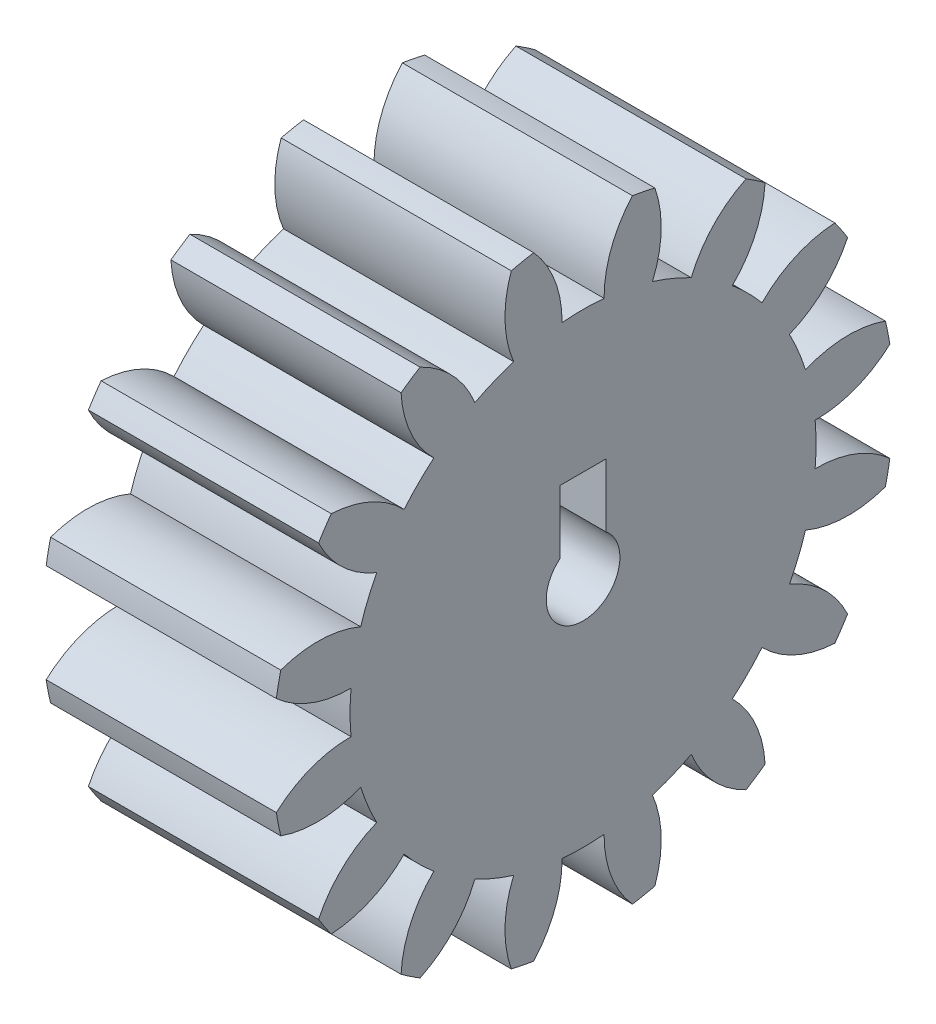
SolidWorks part; units mm, degrees
ref_plane "Plane1" through (0, 0, 0) normal (0, 0, 1) x (1, 0, 0)
ref_plane "Plane2" through (0, 0, 0) normal (0, 1, 0) x (1, 0, 0)
ref_plane "Plane3" through (0, 0, 0) normal (1, 0, 0) x (0, 0, -1)
sketch "HoldingSke" plane through (0, 0, 0) normal (0, 1, 0) x (1, 0, 0)
  line L0 (0, 0) -> (0.6408, -0.1838)
  line L1 (-15, 0) -> (100, 0) construction
  line L2 (0, 0) -> (-2.1039, 2.3779)
  line L3 (0, 0) -> (-11.863, 4.5341)
  line L4 (0, 0) -> (8.3015, 2.3804)
  line L5 (0, 0) -> (-46.8476, -17.4728)
  line L6 (0, 0) -> (-8.2896, -5.593)
  line L7 (-2.1039, 2.3779) -> (8.6586, 51.2059)
  line L8 (-76.2, 54.61) -> (-75.2, 54.61)
  line L9 (-67.7845, 28.3722) -> (-49.3413, 33.142)
  line L10 (-76.2, 71.12) -> (104.1128, 71.12)
  line L11 (0, 0) -> (-10, 0)
  line L12 (-76.2, 101.6) -> (-76.147, 101.6)
  line L13 (24.9733, 27.94) -> (52.9518, 28.4284)
  line L14 (24.9733, 27.94) -> (24.9743, 27.94)
  line L15 (24.9733, 27.94) -> (100.4006, 29.5858)
  line L16 (-63.627, -1.5) -> (-12.827, -1.5)
  circle A0 centre (0, 0) radius 3
  circle A1 centre (0, 0) radius 10.124
  circle A2 centre (0, 0) radius 37.5
  circle A3 centre (0, 0) radius 3
  dimension "MHD" = 20.248
  dimension "Hub_dia" = 75
  dimension "Bore" = 6
  dimension "MBD" = 6
  dimension "Num_teeth" = 16
  dimension "Pitch_radius" = 180.3128
  dimension "Pitch" = 0.6667
  dimension "Width" = 10
  dimension "Overall_len" = 50
  dimension "Show_teeth" = 16
  dimension "Thickness" = 10
  dimension "OAL" = 50.0001
  dimension "T_dim" = 1
  dimension "Ap" = 14.5
  dimension "H" = 19.05
  dimension "Backlash" = 0.053
  dimension "Addendum_fac" = 1
  dimension "Dedendum_fac" = 1.25
  dimension "Clearance_fac" = 0.25
  dimension "Dedendum_add" = 0.001
  dimension "Module" = 1.5
sketch "BasProSke" plane through (0, 0, 0) normal (0, 1, 0) x (1, 0, 0)
  line L0 (-10, 0) -> (60, 0) construction
  line L1 (0, 0) -> (0, 13.5)
  line L2 (0, 0) -> (10, 0)
  line L3 (10, 0) -> (10, 13.5)
  line L4 (10, 13.5) -> (0, 13.5)
  dimension "Diameter" = 27
  dimension "Thickness" = 10
revolve "Base-Revolve" add sketch "BasProSke" angle 360 about L0
sketch "TooCutSke" plane through (0, 0, 0) normal (1, 0, 0) x (0, 0, -1)
  line L1 (0, 0) -> (0, 107) construction
  line L2 (0, 0) -> (-1.2689, 11.9327) construction
  line L3 (0, 0) -> (-4.663, 23.4427) construction
  line L4 (-1.2689, 11.9327) -> (-2.3315, 11.7214) construction
  arc A0 (0.9122, 10.0828) -> (-0.9122, 10.0828) centre (0, 0) ccw
  arc A1 (2.1654, 13.3509) -> (-2.1654, 13.3509) centre (0, 0) ccw
  circle A2 centre (0, 0) radius 12 construction
  circle A3 centre (0, 0) radius 11.6178 construction
  arc A4 (-0.9122, 10.0828) -> (-2.1654, 13.3509) centre (-5.712, 10.1166) ccw
  arc A5 (2.1654, 13.3509) -> (0.9122, 10.0828) centre (5.712, 10.1166) ccw
  dimension "Root_dia" = 20.248
  dimension "Overcut_dia" = 27.0508
  dimension "Pitch_dia" = 24
  dimension "Base_dia" = 23.2355
  dimension "Flank_rad" = 4.8
  dimension "Half_ang" = 11.25
  dimension "Half_CT" = 1.0835
extrude "ToothCut" cut sketch "TooCutSke" along normal through all
fillet "Breaks" [suppressed] radius 0.03
fillet "RootFillets" [suppressed] radius 0.376
pattern_circular "TeethCuts" count 16 every 22.5 about axis through (-10, 0, 0) along (1, 0, 0) of "ToothCut", "RootFillets", "Breaks"
sketch "HubNeaOneSke" [suppressed] plane through (0, 0, 0) normal (-1, 0, 0) x (0, 0, 1)
  circle A0 centre (0, 0) radius 12.7
  dimension "Diameter" = 20.248
extrude "HubNearOne" [suppressed] add sketch "HubNeaOneSke" along normal blind 40.0001
sketch "HubNeaBotSke" [suppressed] plane through (0, 0, 0) normal (-1, 0, 0) x (0, 0, 1)
  circle A0 centre (0, 0) radius 12.7
  dimension "Diameter" = 20.248
extrude "HubNearBoth" [suppressed] add sketch "HubNeaBotSke" along normal blind 20
ref_plane "FarPln" through (10, 0, 0) normal (1, 0, 0) x (0, 0, -1)
sketch "HubFarSke" [suppressed] plane through (12.7, 0, 0) normal (1, 0, 0) x (0, 0, -1)
  circle A0 centre (0, 0) radius 12.7
  dimension "Diameter" = 20.248
extrude "HubFar" [suppressed] add sketch "HubFarSke" along normal blind 20
sketch "BorSke" plane through (0, 0, 0) normal (1, 0, 0) x (0, 0, -1)
  circle A0 centre (0, 0) radius 3
  dimension "Diameter" = 6
extrude "Bore" cut sketch "BorSke" along normal mid plane 100.0001
sketch "KeySke" plane through (0, 0, 0) normal (1, 0, 0) x (0, 0, -1)
  line L0 (-1, 0) -> (-1, 4)
  line L1 (-1, 4) -> (1, 4)
  line L2 (1, 4) -> (1, 0)
  line L3 (0, 0) -> (0, 34) construction
  line L4 (-1, 0) -> (1, 0)
  dimension "Offset" = 4
  dimension "Width" = 2
extrude "Keyway" cut sketch "KeySke" along normal mid plane 100.0001
pattern_circular "Keyway2" [suppressed] count 2 every 90 about axis through (-10, 0, 0) along (1, 0, 0)
sketch "Sketch1" plane through (10, 0, 0) normal (1, 0, 0) x (0, 0, -1)
  line L0 (-1, 4) -> (-1, 2.8284) construction
  line L1 (1, 4) -> (-1, 4) construction
  line L2 (1, 2.8284) -> (1, 4) construction
  line L3 (-1, 4) -> (-1, 1.249)
  line L4 (1, 4) -> (-1, 4)
  line L5 (1, 1.249) -> (1, 4)
  arc A0 (-1, 1.249) -> (1, 1.249) centre (0, 0) ccw
  circle A1 centre (0, 0) radius 5.6987
  dimension "D1" = 3.2
extrude "Boss-Extrude1" add sketch "Sketch1" against normal through all
equation "' \"Module@HoldingSke\" = 6.35"
equation "' \"Num_teeth@HoldingSke\" = 12"
equation "' \"Ap@HoldingSke\" =  20"
equation "' \"Width@HoldingSke\" = 0.5 * 25.4"
equation "' \"Hub_dia@HoldingSke\"= 1 * 25.4"
equation "' \"Overall_len@HoldingSke\" = 1.0 * 25.4"
equation "' \"Bore@HoldingSke\" = 0.75 * 25.4"
equation "' \"T_dim@HoldingSke\" = 0.1 * 25.4"
equation "' \"Width@KeySke\" = 0.25 * 25.4"
equation "' \"Show_teeth@HoldingSke\" = 13"
equation "' \"Backlash@HoldingSke\" = 0.009 * 25.4"
equation "' \"Addendum_fac@HoldingSke\" = 1.0"
equation "' \"Dedendum_fac@HoldingSke\" = 1.25"
equation "' \"Dedendum_add@HoldingSke\" = 0.00005 * 25.4"
equation "' \"Clearance_fac@HoldingSke\" = 0.25"
equation "\"Pitch@HoldingSke\" = 1 / \"Module@HoldingSke\""
equation "\"Overcut_dia@TooCutSke\" = (\"Num_teeth@HoldingSke\" + 2 * \"Addendum_fac@HoldingSke\") / \"Pitch@HoldingSke\" + 0.002 * 25.4"
equation "\"Pitch_dia@TooCutSke\" = \"Num_teeth@HoldingSke\" / \"Pitch@HoldingSke\""
equation "\"Base_dia@TooCutSke\" = \"Num_teeth@HoldingSke\" / \"Pitch@HoldingSke\" * cos((\"Ap@HoldingSke\"  * 3.14159265 / 180))"
equation "\"Root_dia@TooCutSke\" = (\"Num_teeth@HoldingSke\" + 2) / \"Pitch@HoldingSke\" - 2 * (\"Addendum_fac@HoldingSke\" + \"Dedendum_fac@HoldingSke\") / \"Pitch@HoldingSke\" - \"Dedendum_add@HoldingSke\" * 2"
equation "\"Half_ang@TooCutSke\" = 180 / \"Num_teeth@HoldingSke\""
equation "\"Half_CT@TooCutSke\" = \"Num_teeth@HoldingSke\" / \"Pitch@HoldingSke\" * sin((3.14159265 / 2 / \"Num_teeth@HoldingSke\")) / 2 - 7 * \"Backlash@HoldingSke\" / 4"
equation "\"Flank_rad@TooCutSke\" = \"Num_teeth@HoldingSke\" / \"Pitch@HoldingSke\" / 5"
equation "\"Radius@RootFillets\" = \"Clearance_fac@HoldingSke\" / \"Pitch@HoldingSke\" + \"Dedendum_add@HoldingSke\""
equation "\"Break_rad@Breaks\" = 0.02 / \"Pitch@HoldingSke\""
equation "\"Thickness@HoldingSke\" = \"Width@HoldingSke\""
equation "\"OAL@HoldingSke\" = \"Thickness@HoldingSke\""
equation "\"MHD@HoldingSke\" = (\"Num_teeth@HoldingSke\" + 2) / \"Pitch@HoldingSke\" - 2 * (\"Addendum_fac@HoldingSke\" + \"Dedendum_fac@HoldingSke\")  / \"Pitch@HoldingSke\" - \"Dedendum_add@HoldingSke\" * 2"
equation "\"MBD@HoldingSke\" = (\"Num_teeth@HoldingSke\" + 2) / \"Pitch@HoldingSke\" - 2 * (\"Addendum_fac@HoldingSke\" + \"Dedendum_fac@HoldingSke\")  / \"Pitch@HoldingSke\" - \"Dedendum_add@HoldingSke\" * 2 - 0.002 * 25.4"
equation "\"MHD@HoldingSke\" = ((sgn( \"MHD@HoldingSke\" - \"Hub_dia@HoldingSke\" )-1)*( \"MHD@HoldingSke\" - \"Hub_dia@HoldingSke\" ))/-2+ \"Hub_dia@HoldingSke\""
equation "\"MBD@HoldingSke\" = ((sgn( \"MBD@HoldingSke\" - \"Bore@HoldingSke\" )-1)*( \"MBD@HoldingSke\" - \"Bore@HoldingSke\" ))/-2+ \"Bore@HoldingSke\""
equation "\"OAL@HoldingSke\" = ((sgn( \"OAL@HoldingSke\" - \"Overall_len@HoldingSke\" )+1)*( \"OAL@HoldingSke\" - \"Overall_len@HoldingSke\" ))/2 + \"Overall_len@HoldingSke\" + 0.000002 * 25.4"
equation "\"Num_teeth@TeethCuts\" = int( \"Show_teeth@HoldingSke\" ) + 1"
equation "\"Num_teeth@TeethCuts\" = ((sgn( \"Num_teeth@TeethCuts\" - \"Num_teeth@HoldingSke\" )-1)*( \"Num_teeth@TeethCuts\" - \"Num_teeth@HoldingSke\" ))/-2+ \"Num_teeth@HoldingSke\""
equation "\"Num_teeth@TeethCuts\" = ((sgn( \"Num_teeth@TeethCuts\" - 2.0)+1)*( \"Num_teeth@TeethCuts\" - 2.0))/2 +2.0"
equation "\"Angle@TeethCuts\" = 360.0 / \"Num_teeth@HoldingSke\""
equation "\"Diameter@BasProSke\" = (\"Num_teeth@HoldingSke\" + 2 * \"Addendum_fac@HoldingSke\") / \"Pitch@HoldingSke\""
equation "\"Thickness@BasProSke\"  = \"Thickness@HoldingSke\""
equation "' \"Fillet_rad@BasProSke\" =  \"Thickness@HoldingSke\" * 0.05"
equation "\"MHD@HoldingSke\" = ((sgn( \"MHD@HoldingSke\" - \"Root_dia@TooCutSke\" )-1)*( \"MHD@HoldingSke\" - \"Root_dia@TooCutSke\" ))/-2+ \"Root_dia@TooCutSke\""
equation "\"Diameter@HubNeaOneSke\" = \"MHD@HoldingSke\""
equation "\"Length@HubNearOne\" = \"OAL@HoldingSke\" - \"Thickness@BasProSke\""
equation "\"Diameter@HubNeaBotSke\" = \"MHD@HoldingSke\""
equation "\"Length@HubNearBoth\" = ( \"OAL@HoldingSke\" - \"Thickness@BasProSke\" ) / 2.0"
equation "\"Thickness@FarPln\" = \"Thickness@BasProSke\""
equation "\"Diameter@HubFarSke\" = \"MHD@HoldingSke\""
equation "\"Length@HubFar\" = ( \"OAL@HoldingSke\" - \"Thickness@BasProSke\" ) / 2.0"
equation "\"Diameter@BorSke\" = \"MBD@HoldingSke\""
equation "\"D1@Bore\" = \"OAL@HoldingSke\" * 2.0"
equation "\"D1@Keyway\" = \"OAL@HoldingSke\" * 2.0"
equation "\"Offset@KeySke\" = \"T_dim@HoldingSke\" + \"MBD@HoldingSke\" / 2.0"
